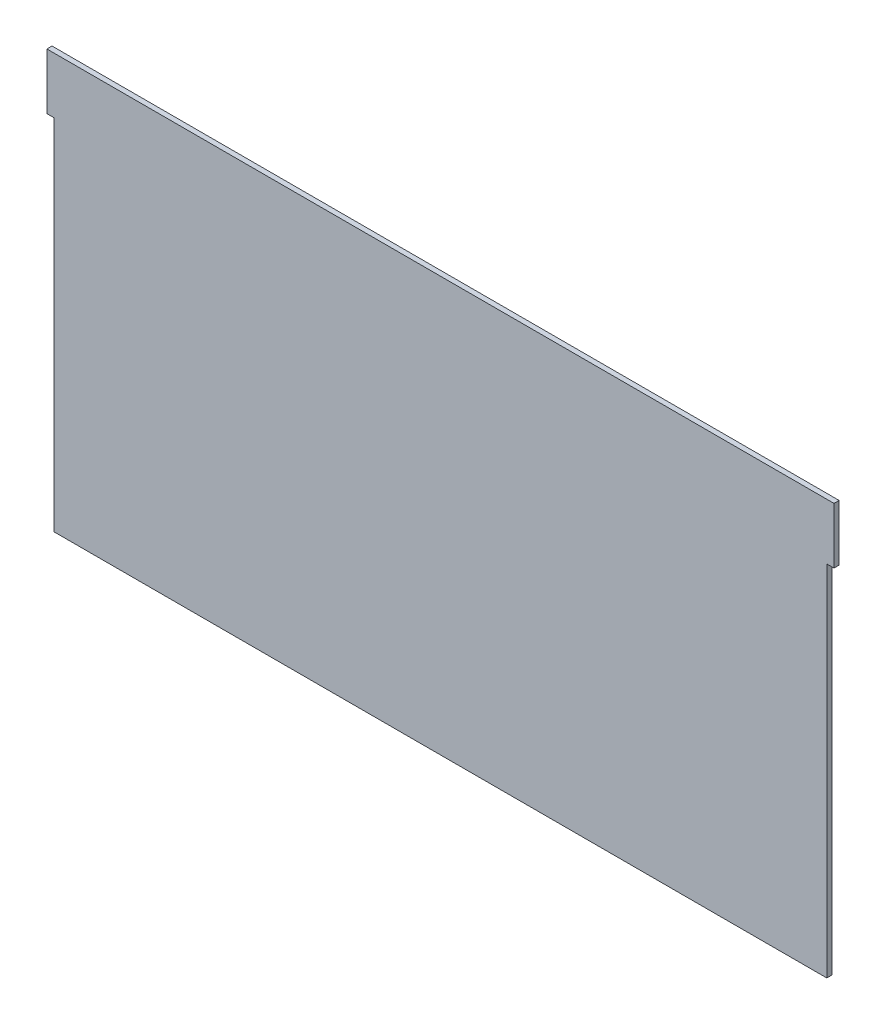
SolidWorks part; units mm, degrees
ref_plane "Front Plane" through (0, 0, 0) normal (0, 0, 1) x (1, 0, 0)
ref_plane "Top Plane" through (0, 0, 0) normal (0, 1, 0) x (1, 0, 0)
ref_plane "Right Plane" through (0, 0, 0) normal (1, 0, 0) x (0, 0, -1)
sketch "Sketch1" plane through (0, 0, 0) normal (0, 0, 1) x (1, 0, 0)
  line L1 (-175.5902, -92.5) -> (175.5902, -92.5)
  line L2 (-175.5902, -92.5) -> (-175.5902, 92.5)
  line L3 (-175.5902, 92.5) -> (175.5902, 92.5)
  line L4 (175.5902, -92.5) -> (175.5902, 92.5)
  line L5 (-175.5902, -92.5) -> (175.5902, 92.5) construction
  line L6 (-175.5902, 92.5) -> (175.5902, -92.5) construction
  point P0 (0, 0)
  dimension "D1" = 351.1803
  dimension "D2" = 185
extrude "Boss-Extrude1" add sketch "Sketch1" along normal blind 2.286
sketch "Sketch2" plane through (0, 0, 2.286) normal (0, 0, 1) x (1, 0, 0)
  line L0 (0, 0) -> (0, -92.5) construction
  line L1 (-175.5902, -92.5) -> (-172.3902, -92.5)
  line L2 (-175.5902, -92.5) -> (-175.5902, 67.5)
  line L3 (-175.5902, 67.5) -> (-172.3902, 67.5)
  line L4 (-172.3902, -92.5) -> (-172.3902, 67.5)
  line L5 (-175.5902, -92.5) -> (175.5902, -92.5) construction
  line L6 (172.3902, -92.5) -> (172.3902, 67.5)
  line L7 (175.5902, 67.5) -> (172.3902, 67.5)
  line L8 (175.5902, -92.5) -> (175.5902, 67.5)
  line L9 (175.5902, -92.5) -> (172.3902, -92.5)
  dimension "D1" = 3.2
  dimension "D2" = 160
extrude "Cut-Extrude1" cut sketch "Sketch2" against normal through all
